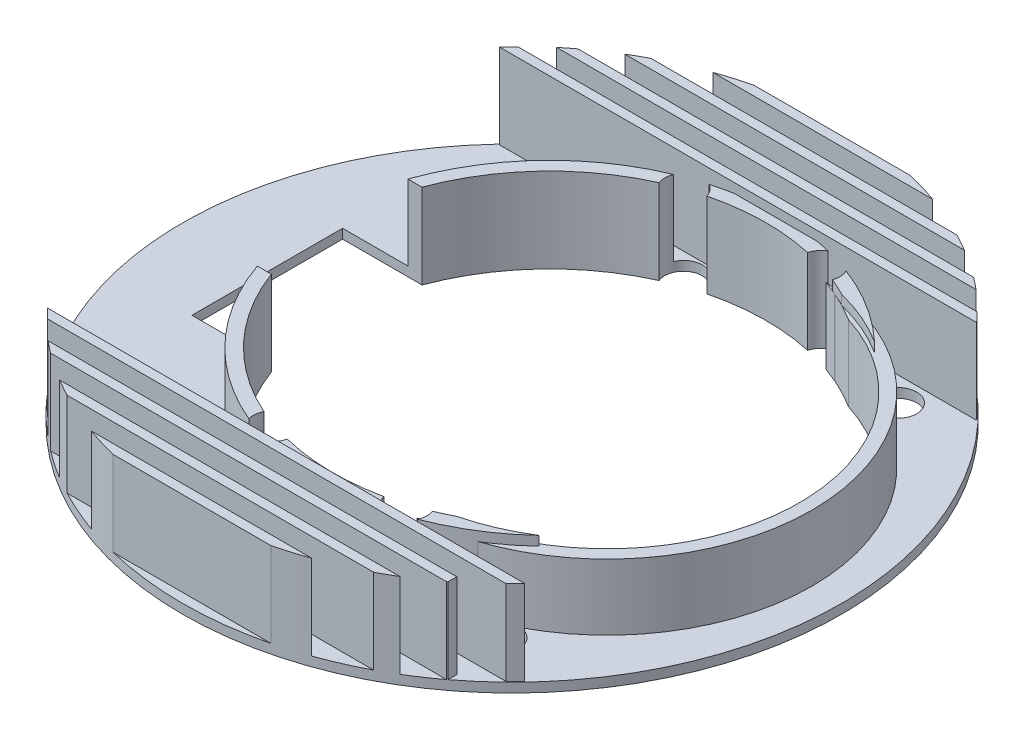
SolidWorks part; units mm, degrees
ref_plane "Front Plane" through (0, 0, 0) normal (0, 0, 1) x (1, 0, 0)
ref_plane "Top Plane" through (0, 0, 0) normal (0, 1, 0) x (1, 0, 0)
ref_plane "Right Plane" through (0, 0, 0) normal (1, 0, 0) x (0, 0, -1)
sketch "Sketch1" plane through (0, 0, 0) normal (0, 1, 0) x (1, 0, 0)
  circle A0 centre (0, 0) radius 17.5
extrude "Boss-Extrude1" add sketch "Sketch1" along normal blind 0.5
sketch "Sketch2" plane through (0, 0.5, 0) normal (0, 1, 0) x (1, 0, 0)
  circle A0 centre (2, 0) radius 11.5
extrude "Cut-Extrude1" cut sketch "Sketch2" against normal blind 0.5
sketch "Sketch3" plane through (0, 0, 0) normal (0, 1, 0) x (1, 0, 0)
  line L1 (2, 4) -> (-13, 4)
  line L2 (2, 4) -> (2, -4)
  line L3 (2, -4) -> (-13, -4)
  line L4 (-13, 4) -> (-13, -4)
extrude "Cut-Extrude4" cut sketch "Sketch3" along normal blind 2.5
sketch "Sketch4" plane through (0, 0, 0) normal (0, 1, 0) x (1, 0, 0)
  circle A0 centre (0, 0) radius 17.2585
  circle A1 centre (0, 0) radius 15.5
sketch "Sketch5" plane through (0, 0.5, 0) normal (0, 1, 0) x (1, 0, 0)
  circle A0 centre (0, 0) radius 14.5
  circle A1 centre (0, 0) radius 14.5
  circle A2 centre (0, 0) radius 14
sketch "Sketch6" plane through (0, 0.5, 0) normal (0, 1, 0) x (1, 0, 0)
  circle A0 centre (0, 0) radius 17.5
  circle A1 centre (0, 0) radius 17
sketch "Sketch7" plane through (0, 0.5, 0) normal (0, 1, 0) x (1, 0, 0)
  line L0 (0, 12.5) -> (0, 13.5)
  line L1 (0, 14) -> (0, 15)
  line L2 (0, 12) -> (12.6696, 12)
  line L3 (12.6696, 12) -> (0, 12)
  line L4 (-12.6696, 12) -> (0, 12)
  line L5 (0, -12) -> (12.6696, -12)
  line L6 (12.6696, -12) -> (0, -12)
  line L7 (0, -12) -> (-12.6696, -12)
  line L8 (0, 12.5) -> (-12.1765, 12.5)
  line L9 (0, -12.5) -> (-12.1765, -12.5)
  line L10 (0, -12.5) -> (12.1765, -12.5)
  line L11 (0, 12.5) -> (12.1765, 12.5)
  line L12 (-15.0094, 14) -> (0, 14)
  line L13 (-15.0094, 14) -> (-15.0094, 13.5)
  line L14 (-15.0094, 13.5) -> (0, 13.5)
  line L15 (0, 14) -> (0, 13.5)
  line L16 (12.6696, 13.5) -> (0, 13.5)
  line L17 (12.6696, 13.5) -> (12.6696, 14)
  line L18 (12.6696, 14) -> (0, 14)
  line L19 (0, 13.5) -> (0, 14)
  line L20 (0, 15.5) -> (0, 16.5)
  line L21 (0, 15) -> (-12.1765, 15)
  line L22 (0, 15) -> (0, 15.5)
  line L23 (0, 15.5) -> (-12.1765, 15.5)
  line L24 (-12.1765, 15) -> (-12.1765, 15.5)
  line L25 (10.5562, 15) -> (0, 15)
  line L26 (10.5562, 15) -> (10.5562, 15.5)
  line L27 (10.5562, 15.5) -> (0, 15.5)
  line L28 (0, 15) -> (0, 15.5)
  line L30 (0, 16.5) -> (-8.985, 16.5)
  line L31 (0, 16.5) -> (0, 17)
  line L32 (0, 17) -> (-8.985, 17)
  line L33 (-8.985, 16.5) -> (-8.985, 17)
  line L34 (9.7018, 17) -> (0, 17)
  line L35 (9.7018, 17) -> (9.7018, 16.5)
  line L36 (9.7018, 16.5) -> (0, 16.5)
  line L37 (0, 17) -> (0, 16.5)
  line L39 (-0.0002, -16.992) -> (12.6693, -16.992)
  line L40 (12.6693, -16.992) -> (-0.0002, -16.992)
  line L41 (-12.6698, -16.992) -> (-0.0002, -16.992)
  line L42 (-0.0002, -16.492) -> (-12.1768, -16.492)
  line L43 (-0.0002, -16.492) -> (12.1763, -16.492)
  line L44 (-15.0096, -14.992) -> (-0.0002, -14.992)
  line L45 (-15.0096, -14.992) -> (-15.0096, -15.492)
  line L46 (-15.0096, -15.492) -> (-0.0002, -15.492)
  line L47 (-0.0002, -14.992) -> (-0.0002, -15.492)
  line L48 (12.6693, -15.492) -> (-0.0002, -15.492)
  line L49 (12.6693, -15.492) -> (12.6693, -14.992)
  line L50 (12.6693, -14.992) -> (-0.0002, -14.992)
  line L51 (-0.0002, -15.492) -> (-0.0002, -14.992)
  line L53 (-0.0002, -13.992) -> (-12.1768, -13.992)
  line L54 (-0.0002, -13.992) -> (-0.0002, -13.492)
  line L55 (-0.0002, -13.492) -> (-12.1768, -13.492)
  line L56 (-12.1768, -13.992) -> (-12.1768, -13.492)
  line L57 (10.556, -13.992) -> (-0.0002, -13.992)
  line L58 (10.556, -13.992) -> (10.556, -13.492)
  line L59 (10.556, -13.492) -> (-0.0002, -13.492)
  line L60 (-0.0002, -13.992) -> (-0.0002, -13.492)
  arc A0 (12.1765, -12.5) -> (12.6696, -12) centre (0, 0) ccw
  arc A1 (12.1765, 12.5) -> (12.6696, 12) centre (0, 0) cw
  arc A2 (-12.1765, -12.5) -> (-12.6696, -12) centre (0, 0) cw
  arc A3 (-12.1765, 12.5) -> (-12.6696, 12) centre (0, 0) ccw
  arc A4 (12.1763, -16.492) -> (12.6693, -16.992) centre (-0.0002, -28.992) cw
  arc A5 (-12.1768, -16.492) -> (-12.6698, -16.992) centre (-0.0002, -28.992) ccw
  circle M10 centre (0, 0) radius 17.5
extrude "Boss-Extrude6" add sketch "Sketch7" along normal blind 4.5 contours A2 L9 L10 A0 L5 L7 | L54 L55 L53 M10 | L58 L59 L54 L57 M10 | L47 L44 L46 M10 | L50 L47 L48 M10 | L43 L42 L41 L39 M10 | L22 L23 L21 M10 | L27 L22 L25 M10 | L15 L12 L14 M10 | L18 L15 L16 M10 | L8 A3 L4 L2 A1 L11 | L31 L32 L30 M10 | L36 L34 L31 M10
sketch "Sketch9" plane through (0, 0.5, 0) normal (0, 1, 0) x (1, 0, 0)
  circle A0 centre (2, 0) radius 12.2
  circle A1 centre (2, 0) radius 11.5
extrude "Boss-Extrude7" add sketch "Sketch9" along normal blind 4
sketch "Sketch10" plane through (0, 0, 0) normal (0, -1, 0) x (1, 0, 0)
  line L1 (-13, -4) -> (-8.7819, -4)
  line L2 (-13, -4) -> (-13, 4)
  line L3 (-13, 4) -> (-8.7819, 4)
  line L4 (-8.7819, -4) -> (-8.7819, 4)
extrude "Cut-Extrude5" cut sketch "Sketch10" against normal blind 6
sketch "Sketch11" plane through (0, 0, 0) normal (0, -1, 0) x (1, 0, 0)
  line L1 (10.0136, -23.0635) -> (5.4296, -23.0635)
  line L3 (5.4296, 24.381) -> (1.1894, 24.381)
  line L7 (-3.0508, 24.381) -> (-6.9472, 24.381)
  circle A0 centre (-117577.4605, -236651.4879) radius 0.0006
  arc A1 (-8.7819, -4) -> (-8.7819, 4) centre (2, 0) ccw construction
  circle A2 centre (-7.3403, -10.1425) radius 1
  circle A3 centre (-1.7676, -10.8653) radius 0.9987
  circle A4 centre (5.4296, -10.9767) radius 0.9987
  circle A6 centre (-7.3403, 9.9174) radius 1
  circle A7 centre (5.4296, 10.9767) radius 1.0326
  circle A8 centre (-1.7676, 10.9767) radius 1
  circle A9 centre (10.0136, 10.6438) radius 1.0081
  circle A10 centre (9.7724, -10.7122) radius 1
  circle A11 centre (0, 0) radius 14.5 construction
extrude "Cut-Extrude7" cut sketch "Sketch11" against normal blind 100 contours A2 | A3 | A4 | A10 | A9 | A7 | A8 | A6
sketch "Sketch12" plane through (0, 0, 0) normal (0, -1, 0) x (1, 0, 0)
  circle A0 centre (4.7204, 0) radius 10.5305
extrude "Cut-Extrude8" cut sketch "Sketch12" against normal blind 10
sketch "Sketch13" plane through (0, 0, 0) normal (0, -1, 0) x (-1, 0, 0)
  circle A0 centre (-5.0448, 0) radius 10.8778
  circle A1 centre (-5.0448, 0) radius 10.2061
extrude "Boss-Extrude8" add sketch "Sketch13" along normal blind 1 and the other way blind 4 separate body
sketch "Sketch15" plane through (0, -1, 0) normal (0, -1, 0) x (1, 0, 0)
  circle A0 centre (0, 0) radius 24.1906
extrude "Cut-Extrude9" cut sketch "Sketch15" against normal blind 1
sketch "Sketch16" plane through (0, 0, 0) normal (0, -1, 0) x (1, 0, 0)
  circle A0 centre (2, 0) radius 11.5
extrude "Cut-Extrude10" cut sketch "Sketch16" against normal blind 10
